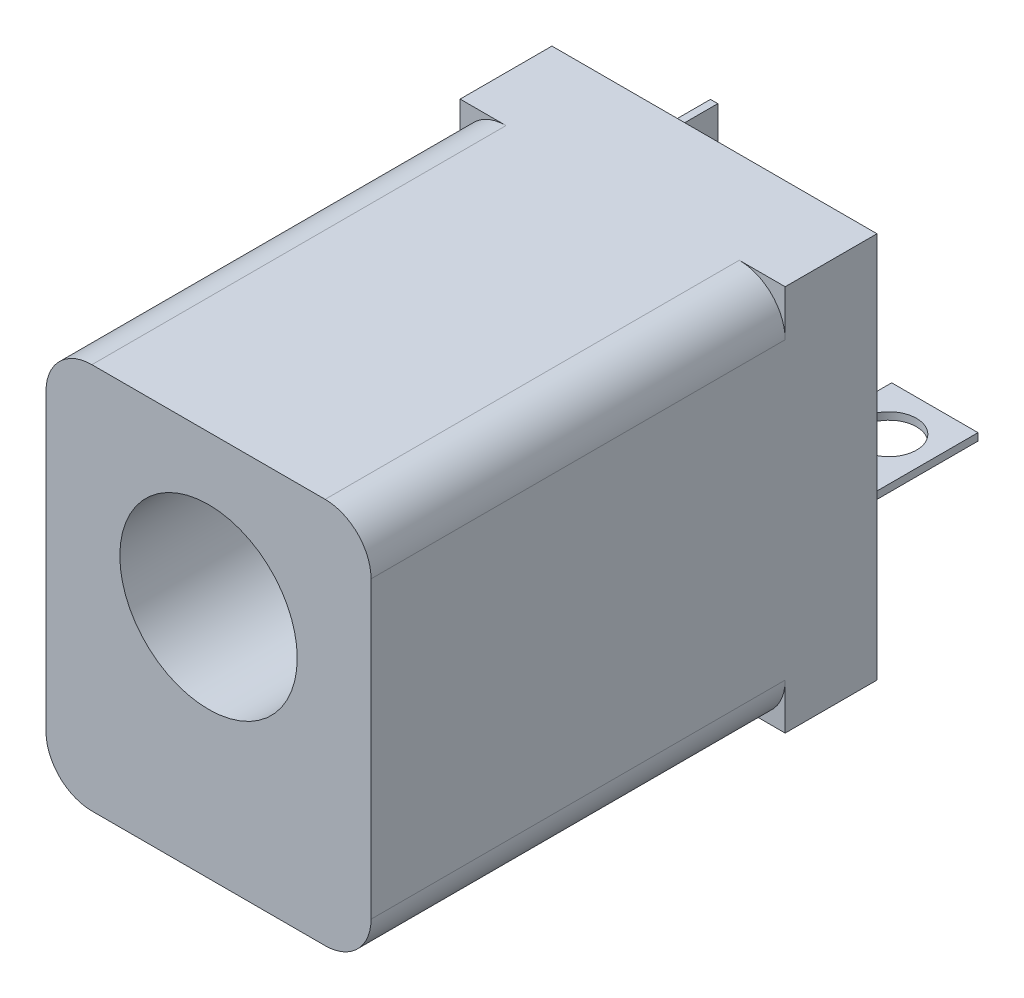
SolidWorks part; units mm, degrees
material "Zinc AC41A Alloy, As Cast"
ref_plane "Front Plane" through (0, 0, 0) normal (0, 0, 1) x (1, 0, 0)
ref_plane "Top Plane" through (0, 0, 0) normal (0, 1, 0) x (1, 0, 0)
ref_plane "Right Plane" through (0, 0, 0) normal (1, 0, 0) x (0, 0, -1)
sketch "Sketch1" plane through (0, 0, 0) normal (0, 0, 1) x (1, 0, 0)
  line L1 (1.27, 0) -> (7.7216, 0)
  line L2 (0, 1.27) -> (0, 9.4234)
  line L3 (1.27, 10.6934) -> (7.7216, 10.6934)
  line L4 (8.9916, 1.27) -> (8.9916, 9.4234)
  arc A0 (0, 1.27) -> (1.27, 0) centre (1.27, 1.27) ccw
  arc A1 (7.7216, 0) -> (8.9916, 1.27) centre (7.7216, 1.27) ccw
  arc A2 (8.9916, 9.4234) -> (7.7216, 10.6934) centre (7.7216, 9.4234) ccw
  arc A3 (1.27, 10.6934) -> (0, 9.4234) centre (1.27, 9.4234) ccw
  point P7 (0, 0)
  point P12 (8.9916, 10.6934)
  point P15 (0, 10.6934)
  dimension "D3" = 1.27
  dimension "D1" = 10.6934
  dimension "D2" = 8.9916
extrude "Boss-Extrude1" add sketch "Sketch1" against normal blind 13.9954
sketch "Sketch2" plane through (0, 0, 0) normal (0, 0, 1) x (1, 0, 0)
  line L0 (8.9916, 1.27) -> (8.9916, 9.4234) construction
  line L2 (1.27, 0) -> (7.7216, 0) construction
  circle A0 centre (4.4958, 6.5024) radius 2.4538
  dimension "D1" = 4.4958
  dimension "D2" = 6.5024
extrude "Cut-Extrude1" cut sketch "Sketch2" against normal blind 9.2456 contours A0
sketch "Sketch3" plane through (0, 0, -13.9954) normal (0, 0, -1) x (-1, 0, 0)
  line L1 (-8.9916, 10.6934) -> (0, 10.6934)
  line L2 (-8.9916, 10.6934) -> (-8.9916, 0)
  line L3 (-8.9916, 0) -> (0, 0)
  line L4 (0, 10.6934) -> (0, 0)
  dimension "D1" = 8.9916
  dimension "D2" = 10.6934
extrude "Boss-Extrude2" add sketch "Sketch3" against normal blind 2.54
sketch "Sketch4" plane through (0, 0, -13.9954) normal (0, 0, -1) x (-1, 0, 0)
  line L0 (-8.9916, 10.6934) -> (0, 10.6934) construction
  line L1 (-0.9804, 8.001) -> (-0.7772, 8.001)
  line L2 (-0.9804, 8.001) -> (-0.9804, 5.0038)
  line L3 (-0.9804, 5.0038) -> (-0.7772, 5.0038)
  line L4 (-0.7772, 8.001) -> (-0.7772, 5.0038)
  line L5 (-4.4069, 1.204) -> (-2.1971, 1.204)
  line L6 (-4.4069, 1.204) -> (-4.4069, 1.0008)
  line L7 (-4.4069, 1.0008) -> (-2.1971, 1.0008)
  line L8 (-2.1971, 1.204) -> (-2.1971, 1.0008)
  line L9 (-8.1788, 3.7186) -> (-5.7912, 3.7186)
  line L10 (-8.1788, 3.7186) -> (-8.1788, 3.5154)
  line L11 (-8.1788, 3.5154) -> (-5.7912, 3.5154)
  line L12 (-5.7912, 3.7186) -> (-5.7912, 3.5154)
  line L13 (-4.4958, 10.6934) -> (-4.4958, 0) construction
  line L14 (0, 0) -> (-8.9916, 0) construction
  line L15 (-0.9804, 6.5024) -> (-0.7772, 6.5024) construction
  line L16 (-6.985, 3.7186) -> (-6.985, 3.5154) construction
  line L17 (-3.302, 1.204) -> (-3.302, 1.0008) construction
  point P19 (-0.9804, 6.5024)
  point P25 (-3.302, 1.0008)
  point P26 (-6.985, 3.5154)
  dimension "D1" = 2.3876
  dimension "D2" = 0.2032
  dimension "D3" = 0.2032
  dimension "D4" = 2.2098
  dimension "D5" = 2.9972
  dimension "D6" = 0.2032
  dimension "D7" = 3.5154
  dimension "D8" = 6.5024
  dimension "D9" = 5.2984
  dimension "D10" = 2.7838
  dimension "D11" = 1.1938
  dimension "D12" = 2.4892
extrude "Boss-Extrude3" add sketch "Sketch4" along normal blind 3.6068
sketch "Sketch5" plane through (0.9804, 0, 0) normal (1, 0, 0) x (0, 0, -1)
  line L0 (16.0782, 8.001) -> (16.0782, 5.0038) construction
  line L1 (17.6022, 8.001) -> (13.9954, 8.001) construction
  line L2 (17.6022, 5.0038) -> (13.9954, 5.0038) construction
  line L3 (17.6022, 8.001) -> (17.6022, 5.0038) construction
  circle A0 centre (16.0782, 6.5024) radius 0.762
  point P10 (16.0782, 6.5024)
  dimension "D1" = 1.524
  dimension "D2" = 1.524
extrude "Cut-Extrude2" cut sketch "Sketch5" against normal up to next
sketch "Sketch6" plane through (0, 3.7186, 0) normal (0, 1, 0) x (1, 0, 0)
  line L0 (5.7912, 16.3322) -> (8.1788, 16.3322) construction
  line L1 (5.7912, 17.6022) -> (5.7912, 13.9954) construction
  line L2 (8.1788, 17.6022) -> (8.1788, 13.9954) construction
  line L3 (5.7912, 17.6022) -> (8.1788, 17.6022) construction
  circle A0 centre (6.985, 16.3322) radius 0.762
  point P8 (6.985, 16.3322)
  dimension "D1" = 1.524
  dimension "D2" = 1.27
extrude "Cut-Extrude3" cut sketch "Sketch6" against normal up to next contours A0
sketch "Sketch7" plane through (0, 1.204, 0) normal (0, 1, 0) x (1, 0, 0)
  line L0 (2.1971, 16.3322) -> (4.4069, 16.3322) construction
  line L1 (2.1971, 17.6022) -> (2.1971, 13.9954) construction
  line L2 (4.4069, 17.6022) -> (4.4069, 13.9954) construction
  line L3 (2.1971, 17.6022) -> (4.4069, 17.6022) construction
  circle A0 centre (3.302, 16.3322) radius 0.635
  point P8 (3.302, 16.3322)
  dimension "D1" = 1.27
  dimension "D2" = 1.27
extrude "Cut-Extrude4" cut sketch "Sketch7" against normal up to next
